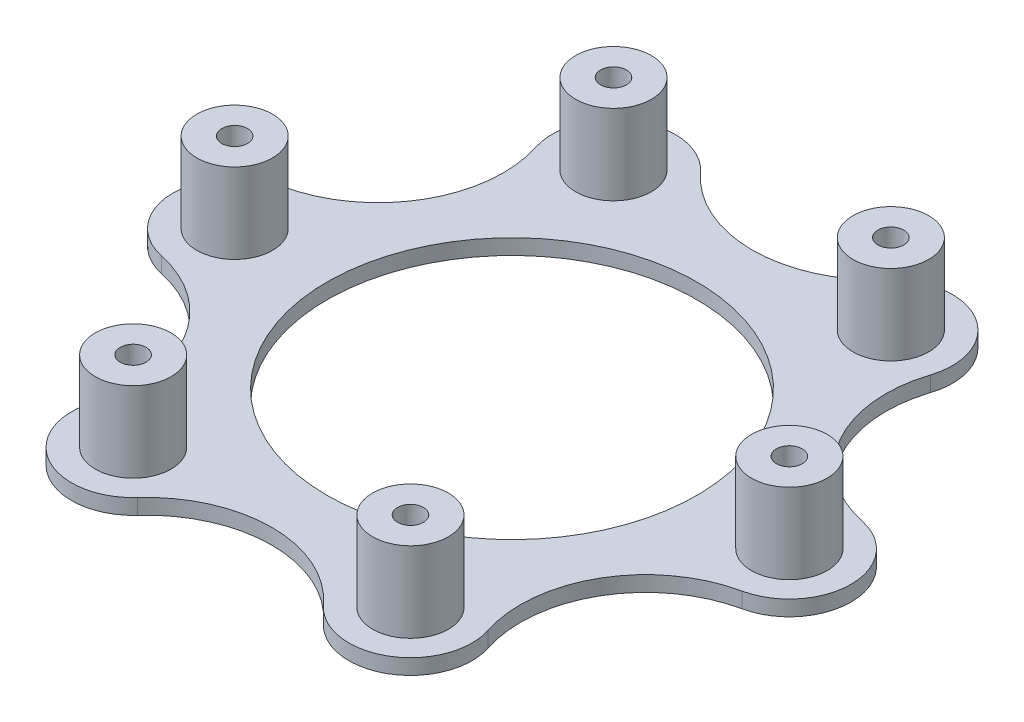
SolidWorks part; units mm, degrees
ref_plane "前视基准面" through (0, 0, 0) normal (0, 0, 1) x (1, 0, 0)
ref_plane "上视基准面" through (0, 0, 0) normal (0, 1, 0) x (1, 0, 0)
ref_plane "右视基准面" through (0, 0, 0) normal (1, 0, 0) x (0, 0, -1)
other "Configuration Table"
sketch "草图2" plane through (0, 0, 0) normal (0, 1, 0) x (1, 0, 0)
  line L1 (45, 0) -> (22.5, 38.9711)
  line L2 (22.5, 38.9711) -> (-22.5, 38.9711)
  line L3 (-22.5, 38.9711) -> (-45, 0)
  line L4 (-45, 0) -> (-22.5, -38.9711)
  line L5 (-22.5, -38.9711) -> (22.5, -38.9711)
  line L6 (22.5, -38.9711) -> (45, 0)
  circle A0 centre (0, 0) radius 38.9711 construction
  circle A1 centre (-22.5, 38.9711) radius 10
  circle A2 centre (0, 0) radius 35
  circle A3 centre (22.5, 38.9711) radius 10
  circle A4 centre (45, 0) radius 10
  circle A5 centre (22.5, -38.9711) radius 10
  circle A6 centre (-22.5, -38.9711) radius 10
  circle A7 centre (-45, 0) radius 10
  circle A8 centre (-51.3411, 29.6418) radius 20.3125
  circle A9 centre (0, 59.2836) radius 20.3125
  circle A10 centre (51.3411, 29.6418) radius 20.3125
  circle A11 centre (51.3411, -29.6418) radius 20.3125
  circle A12 centre (0, -59.2836) radius 20.3125
  circle A13 centre (-51.3411, -29.6418) radius 20.3125
  point P24 (0, 0)
  point P37 (0, 0)
  dimension "D3" = 70
  dimension "D2" = 20
  dimension "D1" = 45
  dimension "D4" = 6
  dimension "D5" = 6
extrude "凸台-拉伸1" add sketch "草图2" along normal blind 2.5 contours A8 L3 A1 | L2 A1 L3 | A9 A1 L2 | A9 L2 A3 | L1 A3 L2 | A10 A3 L1 | A10 L1 A4 | L6 A4 L1 | A11 A4 L6 | A11 L6 A5 | L5 A5 L6 | A12 A5 L5 | A12 L5 A6 | L4 A6 L5 | A13 A6 L4 | A13 L4 A7 | L3 A7 L4 | A8 A7 L3 | A7 A2 A1 L3 | A3 L2 A1 A2 | L3 A1 L2 | L2 A3 L1 | A4 L1 A3 A2 | L1 A4 L6 | A5 L6 A4 A2 | L6 A5 L5 | A6 L5 A5 A2 | L5 A6 L4 | A7 L4 A6 A2 | L4 A7 L3 | A2
sketch "草图3" plane through (0, 2.5, 0) normal (0, 1, 0) x (1, 0, 0)
  line L7 (-45, 0) -> (-22.5, -38.9711) construction
  line L8 (-22.5, -38.9711) -> (22.5, -38.9711) construction
  line L9 (22.5, -38.9711) -> (45, 0) construction
  line L10 (45, 0) -> (22.5, 38.9711) construction
  line L11 (22.5, 38.9711) -> (-22.5, 38.9711) construction
  line L12 (-22.5, 38.9711) -> (-45, 0) construction
  circle A0 centre (0, 0) radius 38.9711 construction
  circle A7 centre (-22.5, 38.9711) radius 2.1
  circle A8 centre (22.5, 38.9711) radius 2.1
  circle A9 centre (45, 0) radius 2.1
  circle A10 centre (22.5, -38.9711) radius 2.1
  circle A11 centre (-22.5, -38.9711) radius 2.1
  circle A12 centre (-45, 0) radius 2.1
  circle A13 centre (0, 0) radius 30
  point P23 (0, 0)
  point P24 (0, 0)
  dimension "D2" = 4.2
  dimension "D1" = 45
  dimension "D4" = 60
  dimension "D3" = 6
extrude "切除-拉伸1" cut sketch "草图3" against normal blind 2.5
sketch "草图4" plane through (0, 2.5, 0) normal (0, 1, 0) x (1, 0, 0)
  circle A0 centre (-22.5, 38.9711) radius 6.15
  circle A1 centre (-22.5, 38.9711) radius 2.1
  circle A2 centre (22.5, 38.9711) radius 6.15
  circle A3 centre (22.5, 38.9711) radius 2.1
  circle A4 centre (45, 0) radius 6.15
  circle A5 centre (45, 0) radius 2.1
  circle A6 centre (22.5, -38.9711) radius 6.15
  circle A7 centre (22.5, -38.9711) radius 2.1
  circle A8 centre (-22.5, -38.9711) radius 6.15
  circle A9 centre (-22.5, -38.9711) radius 2.1
  circle A10 centre (-45, 0) radius 6.15
  circle A11 centre (-45, 0) radius 2.1
  point P22 (0, 0)
  dimension "D1" = 12.3
  dimension "D2" = 6
extrude "凸台-拉伸2" add sketch "草图4" along normal blind 13
